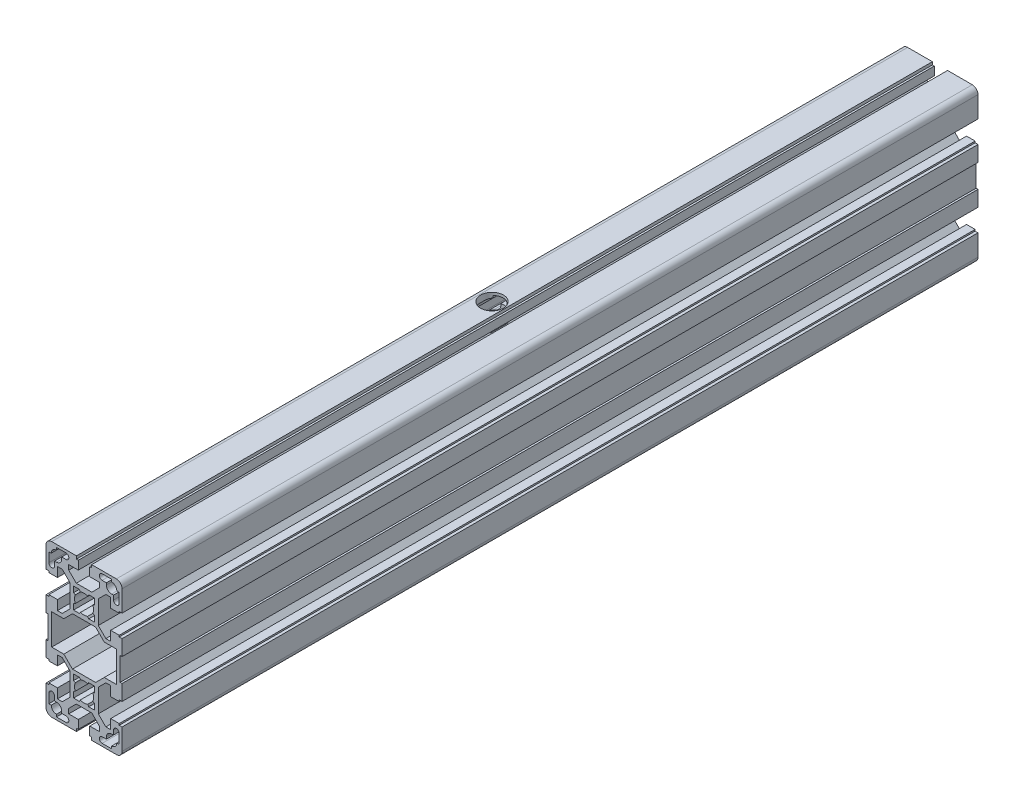
SolidWorks part; units mm, degrees
material "6063-T5"
ref_plane "Front Plane" through (0, 0, 0) normal (0, 0, 1) x (1, 0, 0)
ref_plane "Top Plane" through (0, 0, 0) normal (0, 1, 0) x (1, 0, 0)
ref_plane "Right Plane" through (0, 0, 0) normal (1, 0, 0) x (0, 0, -1)
sketch "Sketch1" plane through (0, 0, 0) normal (0, 0, 1) x (1, 0, 0)
  line L0 (10.6358, -8.0584) -> (17, -8.0584)
  line L1 (19, -6.1084) -> (20, -6.1084)
  line L2 (19, 6.1084) -> (19, -6.1084)
  line L3 (-8.05, -34) -> (-8.05, -31.4642)
  line L4 (-18.5, -34.6084) -> (-18.5, -29.6084)
  line L5 (-20, -25.9084) -> (-20, -37)
  line L6 (17, -8.0584) -> (17, 8.0584)
  line L7 (5.5315, -14.5384) -> (2.4815, -14.5384)
  line L8 (-17, -40) -> (-4, -40)
  line L9 (-3, -34) -> (-8.05, -34)
  line L10 (-11.75, -34.6084) -> (-11.75, -35.6084)
  line L11 (-11.75, -35.6084) -> (-9.5, -35.6084)
  line L12 (-9.5, -38.6084) -> (-14.5, -38.6084)
  line L13 (-14.5, -38.6084) -> (-14.5, -37.3584)
  line L14 (-17.25, -34.6084) -> (-18.5, -34.6084)
  line L15 (4.5833, -18.0017) -> (5.5315, -17.5884)
  line L16 (-4, -40) -> (-4, -38.5)
  line L17 (-4, -38.5) -> (-3, -38.5)
  line L18 (-3, -38.5) -> (-3, -34)
  line L19 (2.4815, -14.5384) -> (1.8428, -15.352)
  line L20 (5.5315, -17.5884) -> (5.5315, -14.5384)
  line L21 (18.5, -15.1084) -> (14, -15.1084)
  line L22 (18.5, -14.3084) -> (18.5, -15.1084)
  line L23 (14, -10.0584) -> (11.4642, -10.0584)
  line L24 (14, -15.1084) -> (14, -10.0584)
  line L25 (20, -14.3084) -> (18.5, -14.3084)
  line L26 (0, 44.6651) -> (0, -44.6651) construction
  line L27 (11.4642, -10.0584) -> (7.5, -14.0226)
  line L28 (5.5, -25.5115) -> (5.5, -22.4615)
  line L29 (2.45, -25.5115) -> (5.5, -25.5115)
  line L30 (1.9672, -24.5968) -> (2.45, -25.5115)
  line L31 (5.5, -22.4615) -> (4.6121, -21.931)
  line L32 (14, -25.1084) -> (18.5, -25.1084)
  line L33 (18.5, -25.1084) -> (18.5, -25.9084)
  line L34 (18.5, -25.9084) -> (20, -25.9084)
  line L35 (11.4642, -30.1584) -> (14, -30.1584)
  line L36 (15.5, -31.8584) -> (14.5, -31.8584)
  line L37 (15.5, -29.6084) -> (15.5, -31.8584)
  line L38 (14, -30.1584) -> (14, -25.1084)
  line L39 (-20, -6.1084) -> (-20, -14.3084)
  line L40 (-6.0858, -12.6084) -> (-10.6358, -8.0584)
  line L41 (-7.5, -14.0226) -> (-7.5, -26.1942)
  line L42 (8.05, -31.4642) -> (4.0858, -27.5)
  line L43 (-7.5, -26.1942) -> (-11.4642, -30.1584)
  line L44 (-8.05, -31.4642) -> (-4.0858, -27.5)
  line L45 (-14, -30.1584) -> (-14, -25.1084)
  line L46 (-15.5, -29.6084) -> (-15.5, -31.8584)
  line L47 (-15.5, -31.8584) -> (-14.5, -31.8584)
  line L48 (-11.4642, -30.1584) -> (-14, -30.1584)
  line L49 (-18.5, -25.9084) -> (-20, -25.9084)
  line L50 (-18.5, -25.1084) -> (-18.5, -25.9084)
  line L51 (-14, -25.1084) -> (-18.5, -25.1084)
  line L52 (7.5, -26.1942) -> (11.4642, -30.1584)
  line L53 (-4.0858, -27.5) -> (4.0858, -27.5)
  line L54 (7.5, -14.0226) -> (7.5, -26.1942)
  line L55 (-5.5, -22.4615) -> (-4.6121, -21.931)
  line L56 (-1.9672, -24.5968) -> (-2.45, -25.5115)
  line L57 (-2.45, -25.5115) -> (-5.5, -25.5115)
  line L58 (-5.5, -25.5115) -> (-5.5, -22.4615)
  line L59 (6.0858, -12.6084) -> (10.6358, -8.0584)
  line L60 (20, -6.1084) -> (20, -14.3084)
  line L61 (3, -38.5) -> (3, -34)
  line L62 (4, -38.5) -> (3, -38.5)
  line L63 (-11.4642, -10.0584) -> (-7.5, -14.0226)
  line L64 (-20, -14.3084) -> (-18.5, -14.3084)
  line L65 (-14, -15.1084) -> (-14, -10.0584)
  line L66 (-14, -10.0584) -> (-11.4642, -10.0584)
  line L67 (-18.5, -14.3084) -> (-18.5, -15.1084)
  line L68 (-18.5, -15.1084) -> (-14, -15.1084)
  line L69 (4, -40) -> (4, -38.5)
  line L70 (-5.5315, -17.5884) -> (-5.5315, -14.5384)
  line L71 (-2.4815, -14.5384) -> (-1.8428, -15.352)
  line L72 (17.25, -34.6084) -> (18.5, -34.6084)
  line L73 (-4.5833, -18.0017) -> (-5.5315, -17.5884)
  line L74 (14.5, -38.6084) -> (14.5, -37.3584)
  line L75 (6.0858, -12.6084) -> (-6.0858, -12.6084)
  line L76 (-5.5315, -14.5384) -> (-2.4815, -14.5384)
  line L77 (9.5, -38.6084) -> (14.5, -38.6084)
  line L78 (11.75, -35.6084) -> (9.5, -35.6084)
  line L79 (-17, -8.0584) -> (-17, 8.0584)
  line L80 (-19, 6.1084) -> (-19, -6.1084)
  line L81 (-19, -6.1084) -> (-20, -6.1084)
  line L82 (-10.6358, -8.0584) -> (-17, -8.0584)
  line L83 (11.75, -34.6084) -> (11.75, -35.6084)
  line L84 (3, -34) -> (8.05, -34)
  line L85 (17, -40) -> (4, -40)
  line L86 (20, -25.9084) -> (20, -37)
  line L87 (18.5, -34.6084) -> (18.5, -29.6084)
  line L88 (8.05, -34) -> (8.05, -31.4642)
  line L89 (8.05, 34) -> (8.05, 31.4642)
  line L90 (18.5, 34.6084) -> (18.5, 29.6084)
  line L91 (20, 25.9084) -> (20, 37)
  line L92 (17, 40) -> (4, 40)
  line L93 (3, 34) -> (8.05, 34)
  line L94 (11.75, 34.6084) -> (11.75, 35.6084)
  line L95 (-10.6358, 8.0584) -> (-17, 8.0584)
  line L96 (-19, 6.1084) -> (-20, 6.1084)
  line L97 (11.75, 35.6084) -> (9.5, 35.6084)
  line L98 (9.5, 38.6084) -> (14.5, 38.6084)
  line L99 (-5.5315, 14.5384) -> (-2.4815, 14.5384)
  line L100 (6.0858, 12.6084) -> (-6.0858, 12.6084)
  line L101 (14.5, 38.6084) -> (14.5, 37.3584)
  line L102 (-4.5833, 18.0017) -> (-5.5315, 17.5884)
  line L103 (17.25, 34.6084) -> (18.5, 34.6084)
  line L104 (-2.4815, 14.5384) -> (-1.8428, 15.352)
  line L105 (-5.5315, 17.5884) -> (-5.5315, 14.5384)
  line L106 (4, 40) -> (4, 38.5)
  line L107 (-18.5, 15.1084) -> (-14, 15.1084)
  line L108 (-18.5, 14.3084) -> (-18.5, 15.1084)
  line L109 (-14, 10.0584) -> (-11.4642, 10.0584)
  line L110 (-14, 15.1084) -> (-14, 10.0584)
  line L111 (-20, 14.3084) -> (-18.5, 14.3084)
  line L112 (-11.4642, 10.0584) -> (-7.5, 14.0226)
  line L113 (4, 38.5) -> (3, 38.5)
  line L114 (3, 38.5) -> (3, 34)
  line L115 (20, 6.1084) -> (20, 14.3084)
  line L116 (6.0858, 12.6084) -> (10.6358, 8.0584)
  line L117 (-5.5, 25.5115) -> (-5.5, 22.4615)
  line L118 (-2.45, 25.5115) -> (-5.5, 25.5115)
  line L119 (-1.9672, 24.5968) -> (-2.45, 25.5115)
  line L120 (-5.5, 22.4615) -> (-4.6121, 21.931)
  line L121 (7.5, 14.0226) -> (7.5, 26.1942)
  line L122 (-4.0858, 27.5) -> (4.0858, 27.5)
  line L123 (7.5, 26.1942) -> (11.4642, 30.1584)
  line L124 (-14, 25.1084) -> (-18.5, 25.1084)
  line L125 (-18.5, 25.1084) -> (-18.5, 25.9084)
  line L126 (-18.5, 25.9084) -> (-20, 25.9084)
  line L127 (-11.4642, 30.1584) -> (-14, 30.1584)
  line L128 (-15.5, 31.8584) -> (-14.5, 31.8584)
  line L129 (-15.5, 29.6084) -> (-15.5, 31.8584)
  line L130 (-14, 30.1584) -> (-14, 25.1084)
  line L131 (-8.05, 31.4642) -> (-4.0858, 27.5)
  line L132 (-7.5, 26.1942) -> (-11.4642, 30.1584)
  line L133 (8.05, 31.4642) -> (4.0858, 27.5)
  line L134 (-7.5, 14.0226) -> (-7.5, 26.1942)
  line L135 (-6.0858, 12.6084) -> (-10.6358, 8.0584)
  line L136 (-20, 6.1084) -> (-20, 14.3084)
  line L137 (14, 30.1584) -> (14, 25.1084)
  line L138 (15.5, 29.6084) -> (15.5, 31.8584)
  line L139 (15.5, 31.8584) -> (14.5, 31.8584)
  line L140 (11.4642, 30.1584) -> (14, 30.1584)
  line L141 (18.5, 25.9084) -> (20, 25.9084)
  line L142 (18.5, 25.1084) -> (18.5, 25.9084)
  line L143 (14, 25.1084) -> (18.5, 25.1084)
  line L144 (5.5, 22.4615) -> (4.6121, 21.931)
  line L145 (1.9672, 24.5968) -> (2.45, 25.5115)
  line L146 (2.45, 25.5115) -> (5.5, 25.5115)
  line L147 (5.5, 25.5115) -> (5.5, 22.4615)
  line L148 (11.4642, 10.0584) -> (7.5, 14.0226)
  line L149 (20, 14.3084) -> (18.5, 14.3084)
  line L150 (14, 15.1084) -> (14, 10.0584)
  line L151 (14, 10.0584) -> (11.4642, 10.0584)
  line L152 (18.5, 14.3084) -> (18.5, 15.1084)
  line L153 (18.5, 15.1084) -> (14, 15.1084)
  line L154 (5.5315, 17.5884) -> (5.5315, 14.5384)
  line L155 (2.4815, 14.5384) -> (1.8428, 15.352)
  line L156 (-3, 38.5) -> (-3, 34)
  line L157 (-4, 38.5) -> (-3, 38.5)
  line L158 (-4, 40) -> (-4, 38.5)
  line L159 (4.5833, 18.0017) -> (5.5315, 17.5884)
  line L160 (-17.25, 34.6084) -> (-18.5, 34.6084)
  line L161 (-14.5, 38.6084) -> (-14.5, 37.3584)
  line L162 (-9.5, 38.6084) -> (-14.5, 38.6084)
  line L163 (-11.75, 35.6084) -> (-9.5, 35.6084)
  line L164 (-11.75, 34.6084) -> (-11.75, 35.6084)
  line L165 (-3, 34) -> (-8.05, 34)
  line L166 (-17, 40) -> (-4, 40)
  line L167 (5.5315, 14.5384) -> (2.4815, 14.5384)
  line L168 (-20, 25.9084) -> (-20, 37)
  line L169 (-18.5, 34.6084) -> (-18.5, 29.6084)
  line L170 (-8.05, 34) -> (-8.05, 31.4642)
  line L171 (19, 6.1084) -> (20, 6.1084)
  line L172 (10.6358, 8.0584) -> (17, 8.0584)
  line L175 (-39.3803, 0) -> (39.3803, 0) construction
  arc A0 (-11.75, -34.6084) -> (-14.5, -31.8584) centre (-14.5, -34.6084) ccw
  arc A1 (15.5, -29.6084) -> (18.5, -29.6084) centre (17, -29.6084) cw
  arc A2 (-9.5, -38.6084) -> (-9.5, -35.6084) centre (-9.5, -37.1084) ccw
  arc A3 (-20, -37) -> (-17, -40) centre (-17, -37) ccw
  arc A4 (-17.25, -34.6084) -> (-14.5, -37.3584) centre (-14.5, -34.6084) ccw
  arc A5 (4.5833, -18.0017) -> (4.6121, -21.931) centre (0, -20) cw
  arc A6 (17.25, -34.6084) -> (14.5, -37.3584) centre (14.5, -34.6084) cw
  arc A7 (20, -37) -> (17, -40) centre (17, -37) cw
  arc A8 (9.5, -38.6084) -> (9.5, -35.6084) centre (9.5, -37.1084) cw
  arc A9 (11.75, -34.6084) -> (14.5, -31.8584) centre (14.5, -34.6084) cw
  arc A10 (-4.5833, -18.0017) -> (-4.6121, -21.931) centre (0, -20) ccw
  arc A11 (-15.5, -29.6084) -> (-18.5, -29.6084) centre (-17, -29.6084) ccw
  arc A12 (-1.9672, -24.5968) -> (1.9672, -24.5968) centre (0, -20) ccw
  arc A13 (1.8428, -15.352) -> (-1.8428, -15.352) centre (0, -20) ccw
  arc A14 (1.8428, 15.352) -> (-1.8428, 15.352) centre (0, 20) cw
  arc A15 (-1.9672, 24.5968) -> (1.9672, 24.5968) centre (0, 20) cw
  arc A16 (-15.5, 29.6084) -> (-18.5, 29.6084) centre (-17, 29.6084) cw
  arc A17 (-4.5833, 18.0017) -> (-4.6121, 21.931) centre (0, 20) cw
  arc A18 (11.75, 34.6084) -> (14.5, 31.8584) centre (14.5, 34.6084) ccw
  arc A19 (9.5, 38.6084) -> (9.5, 35.6084) centre (9.5, 37.1084) ccw
  arc A20 (20, 37) -> (17, 40) centre (17, 37) ccw
  arc A21 (17.25, 34.6084) -> (14.5, 37.3584) centre (14.5, 34.6084) ccw
  arc A22 (4.5833, 18.0017) -> (4.6121, 21.931) centre (0, 20) ccw
  arc A23 (-17.25, 34.6084) -> (-14.5, 37.3584) centre (-14.5, 34.6084) cw
  arc A24 (-20, 37) -> (-17, 40) centre (-17, 37) cw
  arc A25 (-9.5, 38.6084) -> (-9.5, 35.6084) centre (-9.5, 37.1084) cw
  arc A26 (15.5, 29.6084) -> (18.5, 29.6084) centre (17, 29.6084) ccw
  arc A27 (-11.75, 34.6084) -> (-14.5, 31.8584) centre (-14.5, 34.6084) cw
  point P44 (0, -12.6084)
  point P77 (0, -27.5)
  point P143 (0, 27.5)
  point P144 (0, 12.6084)
  point P156 (-19, 0)
  point P157 (-17, 0)
  point P230 (17, 0)
  point P231 (19, 0)
  dimension "D3" = 10
  dimension "D1" = 40
  dimension "D2" = 80
  dimension "D4" = 6
  dimension "D5" = 10
  dimension "D6" = 13
  dimension "D7" = 40
extrude "Extrude1" add sketch "Sketch1" against normal blind 450
sketch "Sketch2" plane through (0, 40, 0) normal (0, 1, 0) x (1, 0, 0)
  circle A0 centre (-10.5, 225) radius 6
extrude "Cut-Extrude1" cut sketch "Sketch2" against normal blind 10
